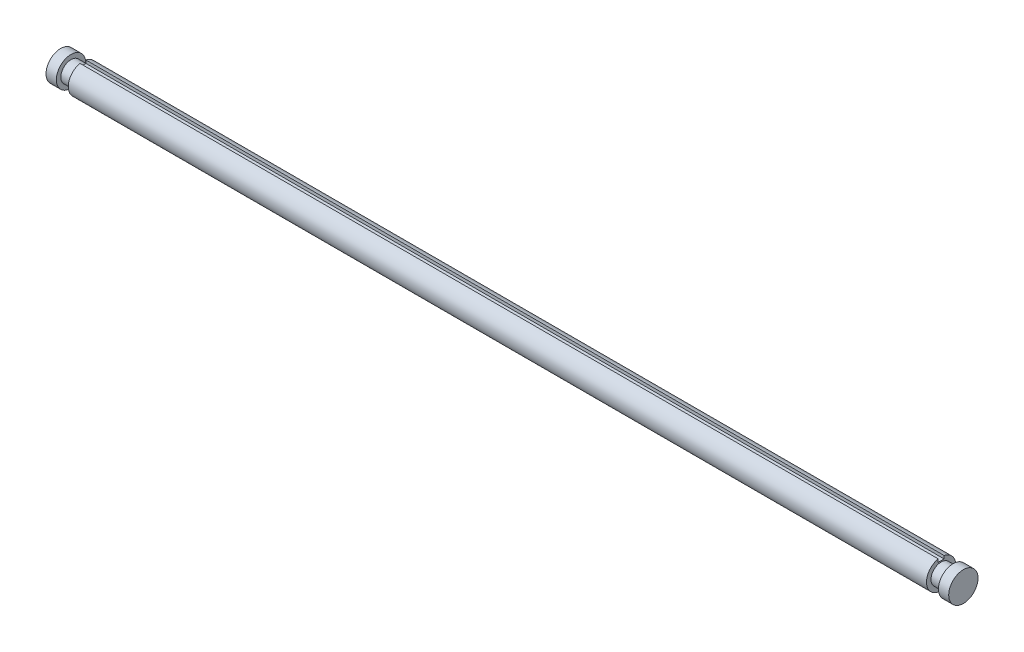
SolidWorks part; units mm, degrees
ref_plane "Front Plane" through (0, 0, 0) normal (1, 0, 0) x (0, 1, 0)
ref_plane "Top Plane" through (0, 0, 0) normal (0, 0, 1) x (0, 1, 0)
ref_plane "Right Plane" through (0, 0, 0) normal (0, 1, 0) x (-1, 0, 0)
sketch "Sketch1" plane through (0, 0, 0) normal (0, 0, 1) x (0, 1, 0)
  line L0 (0, 0) -> (31.7309, 0)
  line L1 (31.7309, 0) -> (31.7309, -22.352)
  line L2 (31.7309, -22.352) -> (22.0218, -22.352)
  line L3 (22.0218, -22.352) -> (22.0218, -48.1584)
  line L4 (22.0218, -48.1584) -> (31.7309, -48.1584)
  line L5 (31.7309, -48.1584) -> (31.7309, -1904.7206)
  line L6 (31.7309, -1904.7206) -> (22.0218, -1904.7206)
  line L7 (22.0218, -1904.7206) -> (22.0218, -1930.527)
  line L8 (22.0218, -1930.527) -> (31.7309, -1930.527)
  line L9 (31.7309, -1930.527) -> (31.7309, -1952.752)
  line L10 (31.7309, -1952.752) -> (0, -1952.752)
  line L11 (0, -1952.752) -> (0, 0)
  line L12 (0, 25.4) -> (0, -1978.152) construction
revolve "Revolve1" add sketch "Sketch1" angle 360 about L12
sketch "Sketch2" plane through (0, 0, 0) normal (1, 0, 0) x (0, 1, 0)
  line L1 (24.6062, -6.35) -> (88.0682, -6.35)
  line L2 (24.6062, -6.35) -> (24.6062, 6.35)
  line L3 (24.6062, 6.35) -> (88.0682, 6.35)
  line L4 (88.0682, -6.35) -> (88.0682, 6.35)
extrude "Cut-Extrude2" cut sketch "Sketch2" along normal blind 1856.5622 from offset 48.1584
